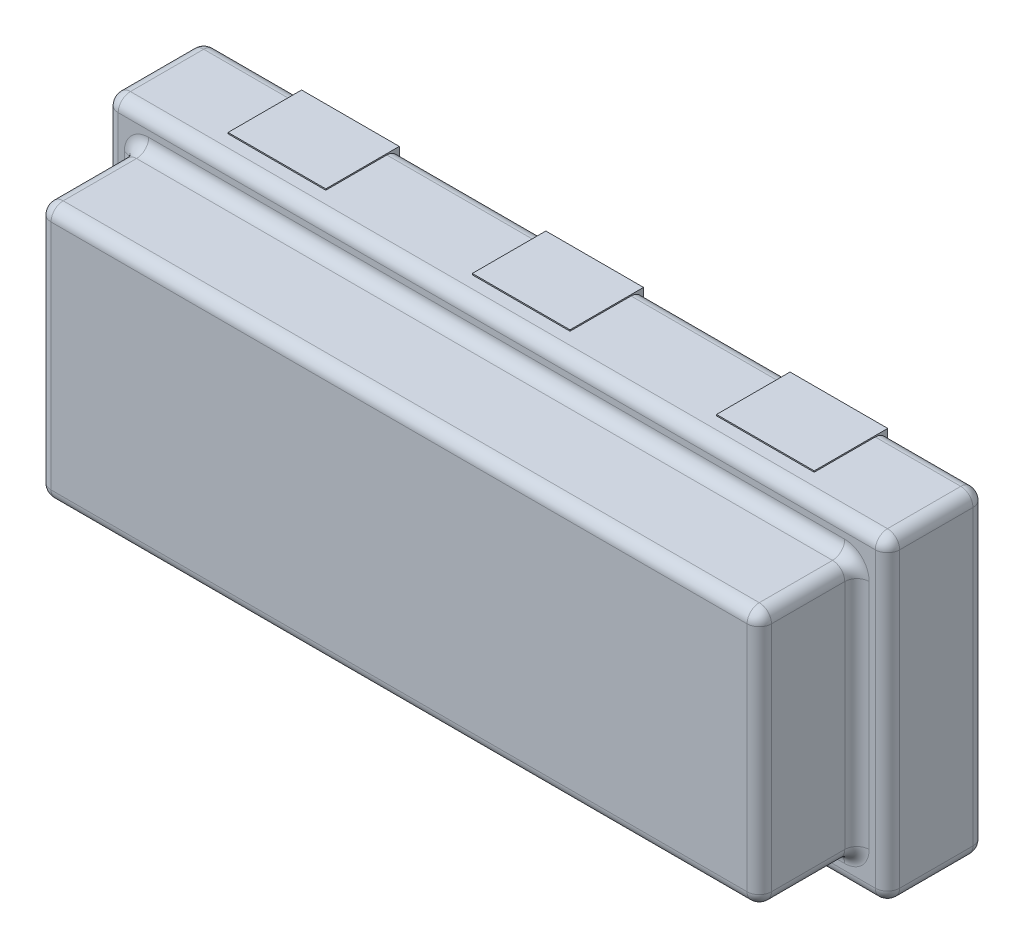
SolidWorks part; units mm, degrees
ref_plane "Plan de face" through (0, 0, 0) normal (0, 0, 1) x (1, 0, 0)
ref_plane "Plan de dessus" through (0, 0, 0) normal (0, 1, 0) x (1, 0, 0)
ref_plane "Plan de droite" through (0, 0, 0) normal (1, 0, 0) x (0, 0, -1)
sketch "Sketch1" plane through (0, 0, 0) normal (0, 0, 1) x (1, 0, 0)
  line L1 (1.6, 0.65) -> (-1.6, 0.65)
  line L2 (1.6, 0.65) -> (1.6, -0.65)
  line L3 (1.6, -0.65) -> (-1.6, -0.65)
  line L4 (-1.6, 0.65) -> (-1.6, -0.65)
  line L5 (1.6, 0.65) -> (-1.6, -0.65) construction
  line L6 (1.6, -0.65) -> (-1.6, 0.65) construction
  point P0 (0, 0)
  dimension "D1" = 3.2
  dimension "D2" = 1.3
extrude "Boss-Extrude1" add sketch "Sketch1" along normal blind 0.4
sketch "Sketch2" plane through (0, 0, 0.4) normal (0, 0, 1) x (1, 0, 0)
  line L1 (1.475, 0.525) -> (-1.475, 0.525)
  line L2 (1.475, 0.525) -> (1.475, -0.525)
  line L3 (1.475, -0.525) -> (-1.475, -0.525)
  line L4 (-1.6, 0.65) -> (-1.6, -0.65)
  line L5 (-1.6, -0.65) -> (1.6, -0.65)
  line L6 (1.6, -0.65) -> (1.6, 0.65)
  line L7 (1.6, 0.65) -> (-1.6, 0.65)
  line L8 (-1.6, 0.65) -> (-1.6, -0.65) construction
  line L9 (-1.6, -0.65) -> (1.6, -0.65) construction
  line L10 (1.6, -0.65) -> (1.6, 0.65) construction
  line L11 (1.6, 0.65) -> (-1.6, 0.65) construction
  line L12 (-1.475, 0.525) -> (-1.475, -0.525)
  line L13 (1.475, 0.525) -> (-1.475, -0.525) construction
  line L14 (1.475, -0.525) -> (-1.475, 0.525) construction
  point P2 (0, 0)
  dimension "D2" = 0.25
  dimension "D3" = 0.25
  dimension "D1" = 0
extrude "Boss-Extrude2" add sketch "Sketch2" along normal blind 0.4
fillet "Fillet1" radius 0.05 24 edges at (1.475, -0.525, 0.6) (1.475, 0.525, 0.6) (-1.475, 0.525, 0.6) (-1.475, -0.525, 0.6) (-1.6, 0, 0) (-1.6, -0.65, 0.2) (0, -0.65, 0) (1.6, -0.65, 0.2) (1.6, 0, 0) (1.6, 0.65, 0.2) (-1.6, 0.65, 0.2) (0, 0.65, 0) (0, -0.525, 0.4) (1.475, 0, 0.4) (0, 0.525, 0.4) (-1.475, 0, 0.4) (0, 0.65, 0.4) (1.6, 0, 0.4) (0, -0.65, 0.4) (-1.6, 0, 0.4) (0, 0.525, 0.8) (1.475, 0, 0.8) (0, -0.525, 0.8) (-1.475, 0, 0.8)
sketch "Sketch3" plane through (0, 0, 0) normal (0, 0, -1) x (-1, 0, 0)
  line L0 (1.2, -0.655) -> (0.8, -0.655)
  line L1 (0.2, -0.655) -> (-0.2, -0.655)
  line L2 (0.2, -0.655) -> (0.2, 0.655)
  line L3 (0.2, 0.655) -> (-0.2, 0.655)
  line L4 (-0.2, -0.655) -> (-0.2, 0.655)
  line L5 (0.2, -0.655) -> (-0.2, 0.655) construction
  line L6 (0.2, 0.655) -> (-0.2, -0.655) construction
  line L7 (1.2, -0.655) -> (1.2, 0.655)
  line L8 (1.2, 0.655) -> (0.8, 0.655)
  line L9 (0.8, -0.655) -> (0.8, 0.655)
  line L10 (1.2, -0.655) -> (0.8, 0.655) construction
  line L11 (1.2, 0.655) -> (0.8, -0.655) construction
  line L12 (-0.8, -0.655) -> (-1.2, -0.655)
  line L13 (-0.8, -0.655) -> (-0.8, 0.655)
  line L14 (-0.8, 0.655) -> (-1.2, 0.655)
  line L15 (-1.2, -0.655) -> (-1.2, 0.655)
  line L16 (-0.8, -0.655) -> (-1.2, 0.655) construction
  line L17 (-0.8, 0.655) -> (-1.2, -0.655) construction
  point P0 (0, 0)
  point P7 (1, 0)
  point P12 (-1, 0)
  dimension "D1" = 1.31
  dimension "D2" = 0.4
  dimension "D3" = 2
  dimension "D4" = 2
extrude "Boss-Extrude3" add sketch "Sketch3" against normal blind 0.3 and the other way blind 0.001
